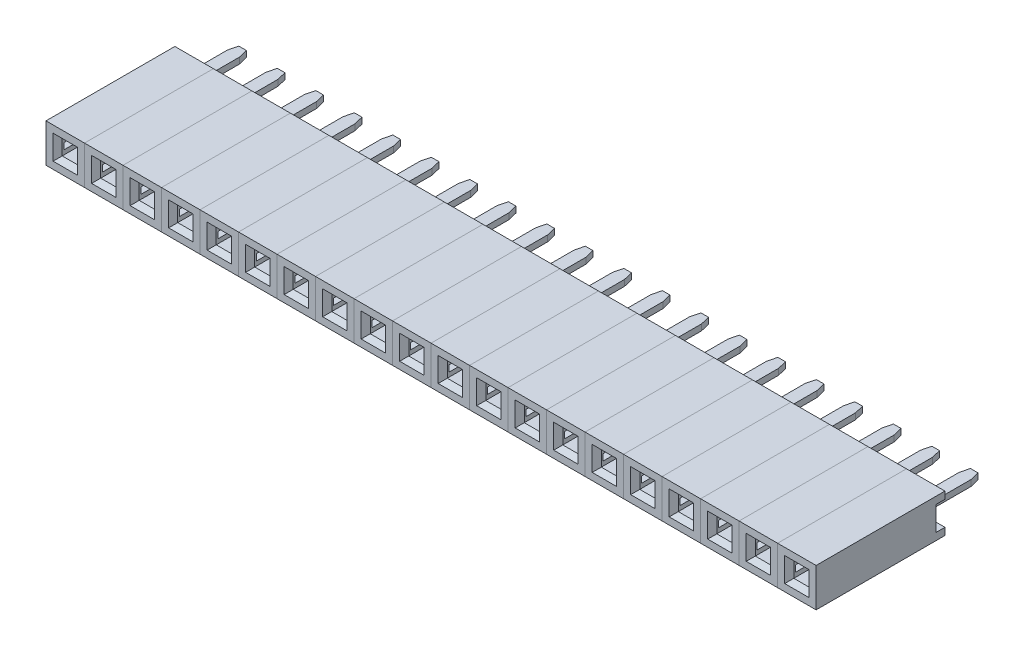
SolidWorks part; units mm, degrees
ref_plane "Спереди" through (0, 0, 0) normal (0, 0, 1) x (1, 0, 0)
ref_plane "Сверху" through (0, 0, 0) normal (0, 1, 0) x (1, 0, 0)
ref_plane "Справа" through (0, 0, 0) normal (1, 0, 0) x (0, 0, -1)
sketch "Эскиз1" plane through (0, 0, 0) normal (0, 0, 1) x (1, 0, 0)
  line L0 (0, 1.27) -> (0, 0) construction
  line L1 (1.27, 2.54) -> (-1.27, 2.54)
  line L2 (1.27, 2.54) -> (1.27, 0)
  line L3 (1.27, 0) -> (-1.27, 0)
  line L4 (-1.27, 2.54) -> (-1.27, 0)
  line L5 (1.27, 2.54) -> (-1.27, 0) construction
  line L6 (1.27, 0) -> (-1.27, 2.54) construction
  dimension "D1" = 2.54
extrude "Бобышка-Вытянуть1" add sketch "Эскиз1" along normal blind 8.5
sketch "Эскиз2" plane through (0, 0, 0) normal (0, 0, -1) x (-1, 0, 0)
  line L0 (0, 1.27) -> (0, 0) construction
  line L1 (1, 1.48) -> (-1, 1.48)
  line L2 (1, 1.48) -> (1, 1.06)
  line L3 (1, 1.06) -> (-1, 1.06)
  line L4 (-1, 1.48) -> (-1, 1.06)
  line L5 (1, 1.48) -> (-1, 1.06) construction
  line L6 (1, 1.06) -> (-1, 1.48) construction
  line L7 (0, 1.27) -> (-1.27, 1.27) construction
  line L8 (-1.27, 0) -> (-1.27, 2.54) construction
  point P0 (0, 1.27)
  dimension "D1" = 2
  dimension "D2" = 0.42
extrude "Вырез-Вытянуть1" cut sketch "Эскиз2" against normal offset from surface (8.08 mm away) 0.42 up to face at (0, 1.27, 8.5)
sketch "Эскиз3" plane through (0, 0, 8.5) normal (0, 0, 1) x (1, 0, 0)
  line L0 (0, 1.27) -> (-1.27, 1.27) construction
  line L1 (-0.5, 0.77) -> (0.5, 0.77)
  line L2 (-0.5, 0.77) -> (-0.5, 1.77)
  line L3 (-0.5, 1.77) -> (0.5, 1.77)
  line L4 (0.5, 0.77) -> (0.5, 1.77)
  line L5 (-0.5, 0.77) -> (0.5, 1.77) construction
  line L6 (-0.5, 1.77) -> (0.5, 0.77) construction
  line L7 (-1.27, 2.54) -> (-1.27, 0) construction
  line L8 (0, 1.27) -> (0, 0) construction
  line L9 (-1.27, 0) -> (1.27, 0) construction
  point P0 (0, 1.27)
  dimension "D1" = 1
  dimension "D2" = 1
extrude "Вырез-Вытянуть2" cut sketch "Эскиз3" against normal offset from surface (6.5 mm away) 2 up to face at (0, 1.27, 0)
sketch "Эскиз4" plane through (-1.27, 0, 0) normal (-1, 0, 0) x (0, 0, 1)
  line L0 (0, 2.54) -> (0, 0) construction
  line L1 (0.6, 0.47) -> (0, 0.47)
  line L2 (0.6, 0.47) -> (0.6, 2.07)
  line L3 (0.6, 2.07) -> (0, 2.07)
  line L4 (0, 0.47) -> (0, 2.07)
  line L5 (0.6, 0.47) -> (0, 2.07) construction
  line L6 (0.6, 2.07) -> (0, 0.47) construction
  line L7 (0.3, 1.27) -> (0, 1.27) construction
  point P0 (0.3, 1.27)
  dimension "D1" = 0.6
  dimension "D2" = 1.6
extrude "Вырез-Вытянуть3" cut sketch "Эскиз4" against normal through all
ref_plane "Плоскость1" through (0, 1.27, 0) normal (0, -1, 0) x (-1, 0, 0)
sketch "Эскиз6" plane through (0, 1.27, 0) normal (0, -1, 0) x (-1, 0, 0)
  line L1 (-1, -8.08) -> (-1, -0.6) construction
  line L2 (1, -8.08) -> (1, -0.6) construction
  line L4 (-1.27, 0) -> (1.27, 0) construction
  line L10 (-1, -0.6) -> (1, -0.6) construction
  line L18 (-0.4, 0) -> (0.4, 0)
  line L19 (-0.6, -0.6) -> (-0.4, -0.6)
  line L20 (-1, -2.6) -> (-1, -0.85)
  line L21 (1, -2.6) -> (1, -0.85)
  line L22 (-0.4, -0.6) -> (-0.4, 0)
  line L23 (0.4, -0.6) -> (0.4, 0)
  line L24 (0, 0) -> (0, -0.6) construction
  line L25 (-1, -2.6) -> (-0.8133, -6.1)
  line L26 (-0.8133, -6.1) -> (-0.45, -6.75)
  line L27 (-0.45, -6.75) -> (-0.3, -6.35)
  line L28 (-0.3, -6.35) -> (-0.5, -2.6)
  line L29 (-0.5, -2.6) -> (-0.5, -1.7)
  line L30 (-0.5, -1.7) -> (0, -1.7) construction
  line L31 (0.5, -1.7) -> (0.5, -2.6)
  line L32 (0.5, -2.6) -> (0.3, -6.35)
  line L33 (0.3, -6.35) -> (0.45, -6.75)
  line L34 (0.45, -6.75) -> (0.8133, -6.1)
  line L35 (0.8133, -6.1) -> (1, -2.6)
  line L36 (-1, -2.6) -> (-0.5, -2.6) construction
  line L37 (0.5, -2.6) -> (-0.5, -2.6) construction
  line L38 (1, -2.6) -> (0.5, -2.6) construction
  line L39 (-0.3, -6.35) -> (0.3, -6.35) construction
  line L40 (-0.45, -6.75) -> (0.45, -6.75) construction
  line L41 (-0.8133, -6.1) -> (0.8133, -6.1) construction
  line L42 (0, -1.7) -> (0.5, -1.7) construction
  line L43 (0, -1.7) -> (0, -0.6) construction
  line L44 (-1, -0.85) -> (-0.6, -0.6)
  line L45 (1, -0.85) -> (0.6, -0.6)
  line L46 (-1, -0.85) -> (1, -0.85) construction
  line L47 (0.4, -0.6) -> (0.6, -0.6)
  arc A0 (-0.5, -1.7) -> (0.5, -1.7) centre (0, -1.7) cw
  dimension "D1" = 0.8
  dimension "D2" = 0.6
  dimension "D3" = 1
  dimension "D4" = 1.2
  dimension "D5" = 0.25
  dimension "D6" = 1.1
  dimension "D7" = 2
  dimension "D8" = 0.4
  dimension "D9" = 0.25
  dimension "D10" = 3.5
  dimension "D11" = 0.9
  dimension "D12" = 1.2
extrude "Бобышка-Вытянуть2" add sketch "Эскиз6" along normal mid plane 0.4 separate body contours L29 A0 L31 L32 L33 L34 L35 L21 L45 L19 L44 L20 L25 L26 L27 L28 | L19 L23 L18 L22
chamfer "Фаска1" distance 0.3 angle 45 4 edges at (0, 0.77, 8.5) (0.5, 1.27, 8.5) (0, 1.77, 8.5) (-0.5, 1.27, 8.5)
sketch "Sketch1" plane through (0, 0, 0) normal (0, 0, -1) x (-1, 0, 0)
  line L1 (-0.4, 1.47) -> (0.4, 1.47)
  line L2 (-0.4, 1.47) -> (-0.4, 1.07)
  line L3 (-0.4, 1.07) -> (0.4, 1.07)
  line L4 (0.4, 1.47) -> (0.4, 1.07)
extrude "Boss-Extrude1" add sketch "Sketch1" along normal blind 3.2
sketch "Sketch2" plane through (0, 1.47, 0) normal (0, 1, 0) x (1, 0, 0)
  line L0 (-0.4, 2.6) -> (0.4, 2.6) construction
  line L1 (-0.4, -0.6) -> (-0.4, 3.2) construction
  line L2 (0.4, -0.6) -> (0.4, 3.2) construction
  line L3 (-0.4, 3.2) -> (0.4, 3.2) construction
  line L4 (0, 3.2) -> (0, 2.6) construction
  line L5 (-0.25, 3.2) -> (-0.25, 2.6) construction
  line L6 (-0.25, 3.2) -> (-0.4, 2.6)
  line L7 (-0.4, 2.6) -> (-0.5333, 2.6)
  line L8 (-0.5333, 2.6) -> (-0.5333, 3.3233)
  line L9 (-0.5333, 3.3233) -> (-0.25, 3.3233)
  line L10 (-0.25, 3.3233) -> (-0.25, 3.2)
  line L11 (-0.25, 3.2) -> (-0.2501, 3.2095)
  line L12 (0.4, 2.6) -> (0.5333, 2.6)
  line L13 (0.25, 3.2) -> (0.4, 2.6)
  line L14 (0.25, 3.3233) -> (0.25, 3.2)
  line L15 (0.5333, 2.6) -> (0.5333, 3.3233)
  line L16 (0.5333, 3.3233) -> (0.25, 3.3233)
  dimension "D1" = 0.6
  dimension "D2" = 0.25
extrude "Cut-Extrude1" cut sketch "Sketch2" against normal blind 1
pattern_linear "LPattern1" count 20 spacing 2.54 along (1, 0, 0) of bodies 127
